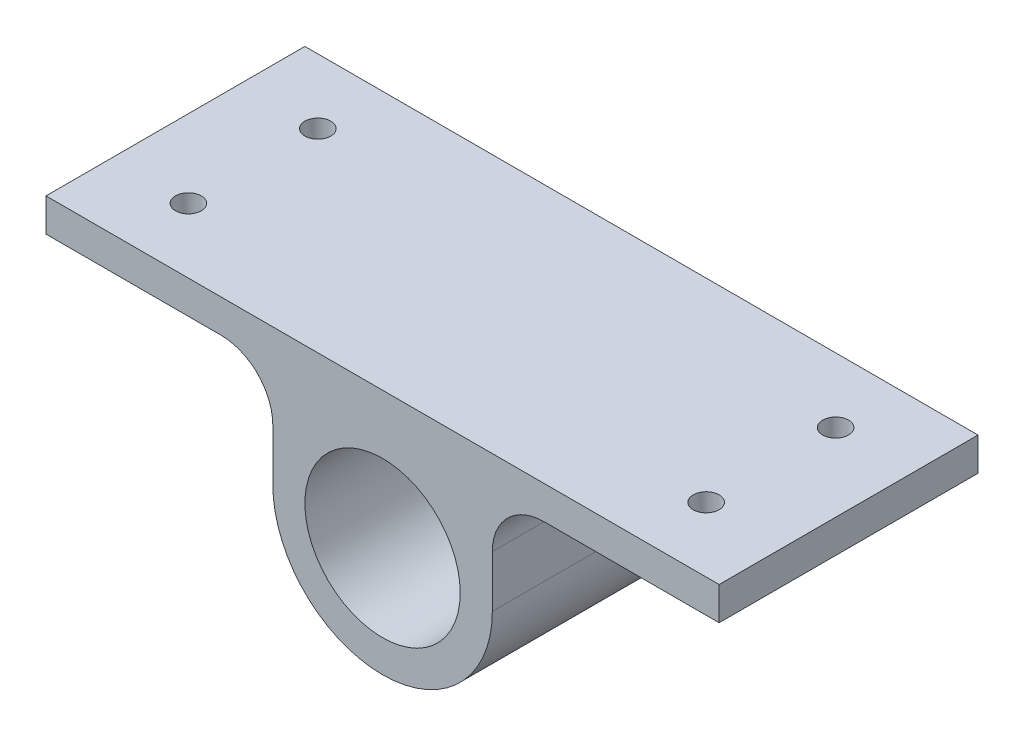
SolidWorks part; units mm, degrees
ref_plane "Front Plane" through (0, 0, 0) normal (0, 0, 1) x (1, 0, 0)
ref_plane "Top Plane" through (0, 0, 0) normal (0, 1, 0) x (1, 0, 0)
ref_plane "Right Plane" through (0, 0, 0) normal (1, 0, 0) x (0, 0, -1)
sketch "Sketch1" plane through (0, 0, 0) normal (0, 0, 1) x (1, 0, 0)
  line L0 (-288.6174, 0) -> (249.6151, 0) construction
  line L1 (0, 139.1084) -> (0, -150.8091) construction
  line L2 (-106, 0) -> (-106, 50)
  line L3 (-156, 100) -> (-325, 100)
  line L4 (-325, 100) -> (-325, 132)
  line L5 (-325, 132) -> (325, 132)
  line L6 (106, 0) -> (106, 50)
  line L7 (156, 100) -> (325, 100)
  line L8 (325, 100) -> (325, 132)
  circle A0 centre (0, 0) radius 75
  arc A1 (-106, 0) -> (106, 0) centre (0, 0) ccw
  arc A2 (-106, 50) -> (-156, 100) centre (-156, 50) ccw
  arc A3 (106, 50) -> (156, 100) centre (156, 50) cw
  point P21 (0, 132)
  dimension "D1" = 150
  dimension "D2" = 212
  dimension "D3" = 50
  dimension "D4" = 32
  dimension "D5" = 325
  dimension "D6" = 132
  dimension "D7" = 325
extrude "Boss-Extrude1" add sketch "Sketch1" along normal mid plane 250
sketch "Sketch2" plane through (0, 132, 0) normal (0, 1, 0) x (1, 0, 0)
  line L0 (0, 103.1561) -> (0, -125) construction
  line L1 (325, -125) -> (-325, -125) construction
  line L2 (-162.1025, 0) -> (157.892, 0) construction
  line L3 (-325, -125) -> (-325, 125) construction
  line L4 (325, 125) -> (-325, 125) construction
  circle A0 centre (-250, 62.5) radius 12.5
  circle A1 centre (250, 62.5) radius 12.5
  circle A2 centre (250, -62.5) radius 12.5
  circle A3 centre (-250, -62.5) radius 12.5
  dimension "D3" = 25
  dimension "D1" = 75
  dimension "D2" = 62.5
  dimension "D4" = 125
  dimension "D5" = 500
extrude "Cut-Extrude1" cut sketch "Sketch2" against normal through all
